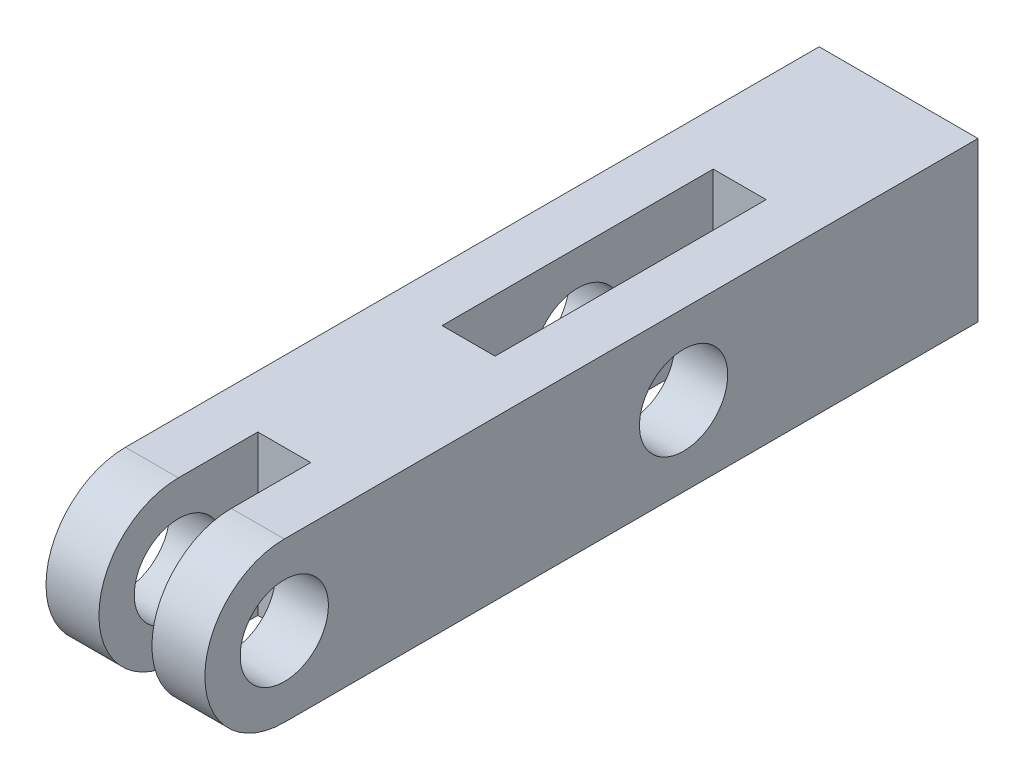
SolidWorks part; units mm, degrees
ref_plane "Front Plane" through (0, 0, 0) normal (0, 0, 1) x (1, 0, 0)
ref_plane "Top Plane" through (0, 0, 0) normal (0, 1, 0) x (1, 0, 0)
ref_plane "Right Plane" through (0, 0, 0) normal (1, 0, 0) x (0, 0, -1)
sketch "Sketch1" plane through (0, 0, 0) normal (0, 0, 1) x (1, 0, 0)
  line L1 (0, 0) -> (9, 0)
  line L2 (0, 0) -> (0, 9)
  line L3 (0, 9) -> (9, 9)
  line L4 (9, 0) -> (9, 9)
  line L5 (9, 9) -> (6, 9)
  line L6 (9, 9) -> (9, 0)
  line L7 (9, 0) -> (6, 0)
  line L8 (6, 9) -> (6, 0)
  line L9 (0, 9) -> (3, 9)
  line L10 (0, 9) -> (0, 0)
  line L11 (0, 0) -> (3, 0)
  line L12 (3, 9) -> (3, 0)
  dimension "D1" = 9
  dimension "D2" = 9
  dimension "D3" = 3
  dimension "D4" = 3
extrude "Boss-Extrude1" add sketch "Sketch1" along normal blind 9 contours L12 L3 L2 L1 | L3 L8 L1 L4
sketch "Sketch2" plane through (0, 0, 0) normal (0, 0, -1) x (-1, 0, 0)
  line L1 (0, 9) -> (-9, 9)
  line L2 (0, 9) -> (0, 0)
  line L3 (0, 0) -> (-9, 0)
  line L4 (-9, 9) -> (-9, 0)
extrude "Boss-Extrude2" add sketch "Sketch2" along normal blind 10.44
sketch "Sketch3" plane through (0, 0, -10.44) normal (0, 0, -1) x (-1, 0, 0)
  line L0 (-9, 0) -> (0, 0) construction
  line L1 (-9, 9) -> (-6, 9)
  line L2 (-9, 9) -> (-9, 0)
  line L3 (-9, 0) -> (-6, 0)
  line L4 (-6, 9) -> (-6, 0)
  line L6 (0, 9) -> (-3, 9)
  line L7 (0, 9) -> (0, 0)
  line L8 (0, 0) -> (-3, 0)
  line L9 (-3, 9) -> (-3, 0)
  dimension "D1" = 3
  dimension "D2" = 3
extrude "Boss-Extrude3" add sketch "Sketch3" along normal blind 15.36
sketch "Sketch4" plane through (0, 0, -25.8) normal (0, 0, -1) x (-1, 0, 0)
  line L1 (-9, 9) -> (0, 9)
  line L2 (-9, 9) -> (-9, 0)
  line L3 (-9, 0) -> (0, 0)
  line L4 (0, 9) -> (0, 0)
extrude "Boss-Extrude4" add sketch "Sketch4" along normal blind 9
sketch "Sketch5" plane through (9, 0, 0) normal (1, 0, 0) x (0, 0, -1)
  line L0 (18.12, 9) -> (18.12, 0) construction
  line L1 (34.8, 9) -> (-9, 9) construction
  line L2 (34.8, 0) -> (-9, 0) construction
  line L3 (-9, 0) -> (-9, 9) construction
  circle A0 centre (18.12, 4.5) radius 2.5
  dimension "D2" = 5
  dimension "D1" = 27.12
extrude "Cut-Extrude1" cut sketch "Sketch5" against normal through all
sketch "Sketch6" plane through (9, 0, 0) normal (1, 0, 0) x (0, 0, -1)
  line L0 (-4.5, 9) -> (-4.5, 0) construction
  line L1 (34.8, 9) -> (-9, 9) construction
  line L2 (34.8, 0) -> (-9, 0) construction
  line L3 (-9, 0) -> (-9, 9) construction
  arc A0 (-4.5, 9) -> (-4.5, 0) centre (-4.5, 4.5) ccw
  circle A1 centre (-4.5, 4.5) radius 2.5
  line M3 (34.8, 9) -> (-9, 9)
  line M4 (-9, 9) -> (-9, 0)
  line M5 (-9, 0) -> (34.8, 0)
  dimension "D2" = 5
  dimension "D1" = 4.5
extrude "Cut-Extrude5" cut sketch "Sketch6" against normal through all contours A0 M3 M4 | A0 M4 M5 | L0 A1 | A1 L0
